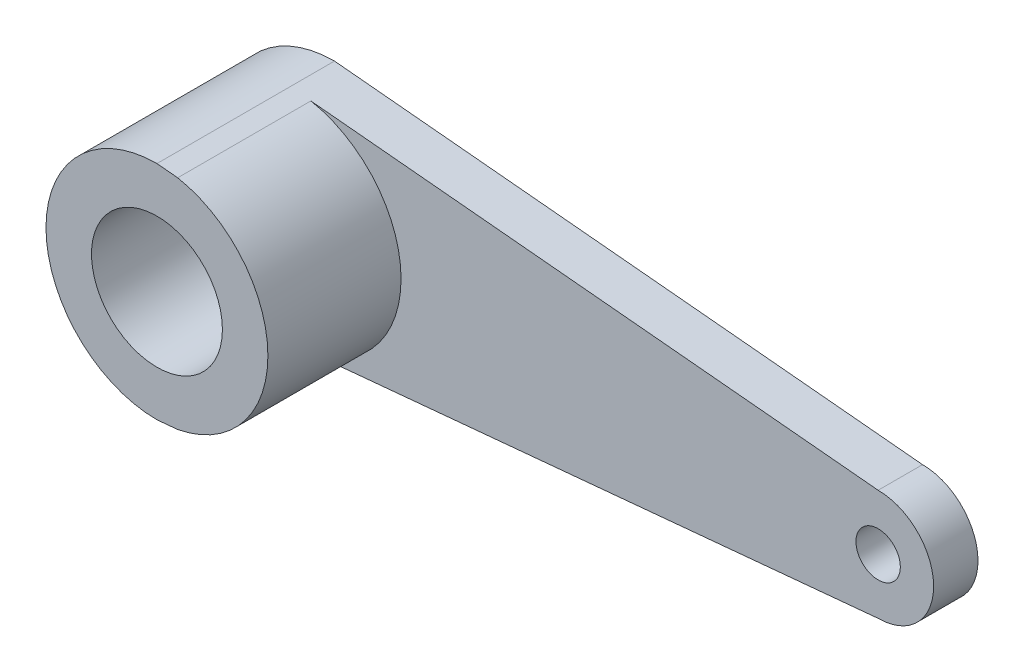
SolidWorks part; units mm, degrees
ref_plane "Plan de face" through (0, 0, 0) normal (0, 0, 1) x (1, 0, 0)
ref_plane "Plan de dessus" through (0, 0, 0) normal (0, 1, 0) x (1, 0, 0)
ref_plane "Plan de droite" through (0, 0, 0) normal (1, 0, 0) x (0, 0, -1)
sketch "Esquisse1" plane through (0, 0, 0) normal (0, 0, 1) x (1, 0, 0)
  line L0 (0, 5) -> (26.5, 2.5)
  line L1 (26.5, 2.5) -> (26.5, -2.5)
  line L2 (26.5, -2.5) -> (0, -5)
  line L3 (0, 5) -> (0, -5) construction
  line L4 (-5, 0) -> (29, 0) construction
  circle A0 centre (0, 0) radius 2.95
  arc A1 (0, 5) -> (0, -5) centre (0, 0) ccw
  arc A2 (26.5, 2.5) -> (26.5, -2.5) centre (26.5, 0) cw
  circle A3 centre (26.5, 0) radius 1
  point P9 (26.5, 0)
  dimension "D1" = 34
  dimension "D2" = 5.9
  dimension "D3" = 5
  dimension "D4" = 2.5
  dimension "D5" = 2
extrude "Boss.-Extru.1" add sketch "Esquisse1" along normal blind 8 contours A3 L1 L0 A1 L2 A0 | A3 L1 A2
sketch "Esquisse2" plane through (0, 0, 8) normal (0, 0, 1) x (1, 0, 0)
  line L0 (0, 5) -> (26.7338, 2.489)
  line L1 (26.7338, 2.489) -> (26.5, -2.5)
  line L2 (26.5, -2.5) -> (0, -5)
  line L3 (0, 5) -> (0, -5)
  circle A0 centre (0, 0) radius 5
  circle A1 centre (26.5, 0) radius 2.5
  circle M3 centre (26.5, 0) radius 1
  arc M4 (26.5, -2.5) -> (26.5, 2.5) centre (26.5, 0) ccw
  line M5 (26.5, 2.5) -> (0, 5)
  dimension "D1" = 5
extrude "Enlèv. mat.-Extru.1" cut sketch "Esquisse2" against normal blind 6 contours A1 A0 L2 M5 | A1 L1 M4 M3 | L1 M4 M3
